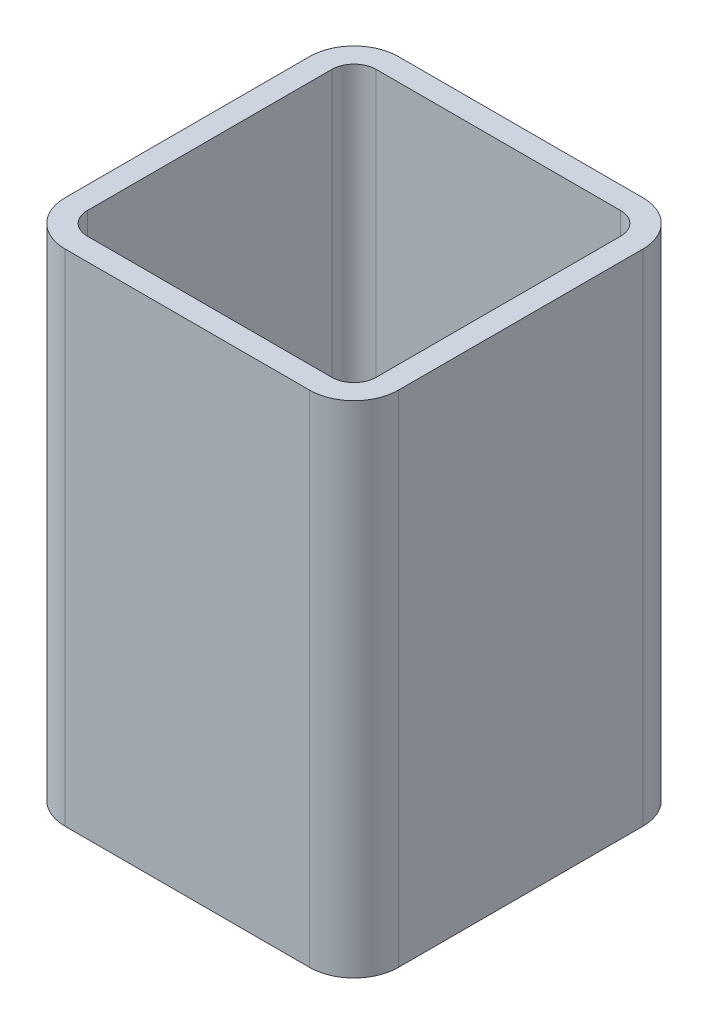
SolidWorks part; units mm, degrees
ref_plane "前视基准面" through (0, 0, 0) normal (0, 0, 1) x (1, 0, 0)
ref_plane "上视基准面" through (0, 0, 0) normal (0, 1, 0) x (1, 0, 0)
ref_plane "右视基准面" through (0, 0, 0) normal (1, 0, 0) x (0, 0, -1)
sketch "草图1" plane through (0, 0, 0) normal (0, 1, 0) x (1, 0, 0)
  line L0 (4, 2) -> (26, 2)
  line L1 (4, 0) -> (26, 0)
  line L2 (0, 4) -> (0, 26)
  line L3 (4, 30) -> (26, 30)
  line L4 (30, 4) -> (30, 26)
  line L5 (28, 4) -> (28, 26)
  line L6 (4, 28) -> (26, 28)
  line L7 (2, 4) -> (2, 26)
  arc A0 (4, 0) -> (0, 4) centre (4, 4) cw
  arc A1 (26, 0) -> (30, 4) centre (26, 4) ccw
  arc A2 (26, 30) -> (30, 26) centre (26, 26) cw
  arc A3 (0, 26) -> (4, 30) centre (4, 26) cw
  arc A4 (26, 2) -> (28, 4) centre (26, 4) ccw
  arc A5 (26, 28) -> (28, 26) centre (26, 26) cw
  arc A6 (2, 26) -> (4, 28) centre (4, 26) cw
  arc A7 (4, 2) -> (2, 4) centre (4, 4) cw
  point P7 (0, 0)
  point P10 (30, 0)
  point P13 (30, 30)
  point P16 (0, 30)
  dimension "D3" = 4
  dimension "D1" = 30
  dimension "D2" = 30
  dimension "D4" = 2
extrude "凸台-拉伸1" add sketch "草图1" along normal mid plane 45
